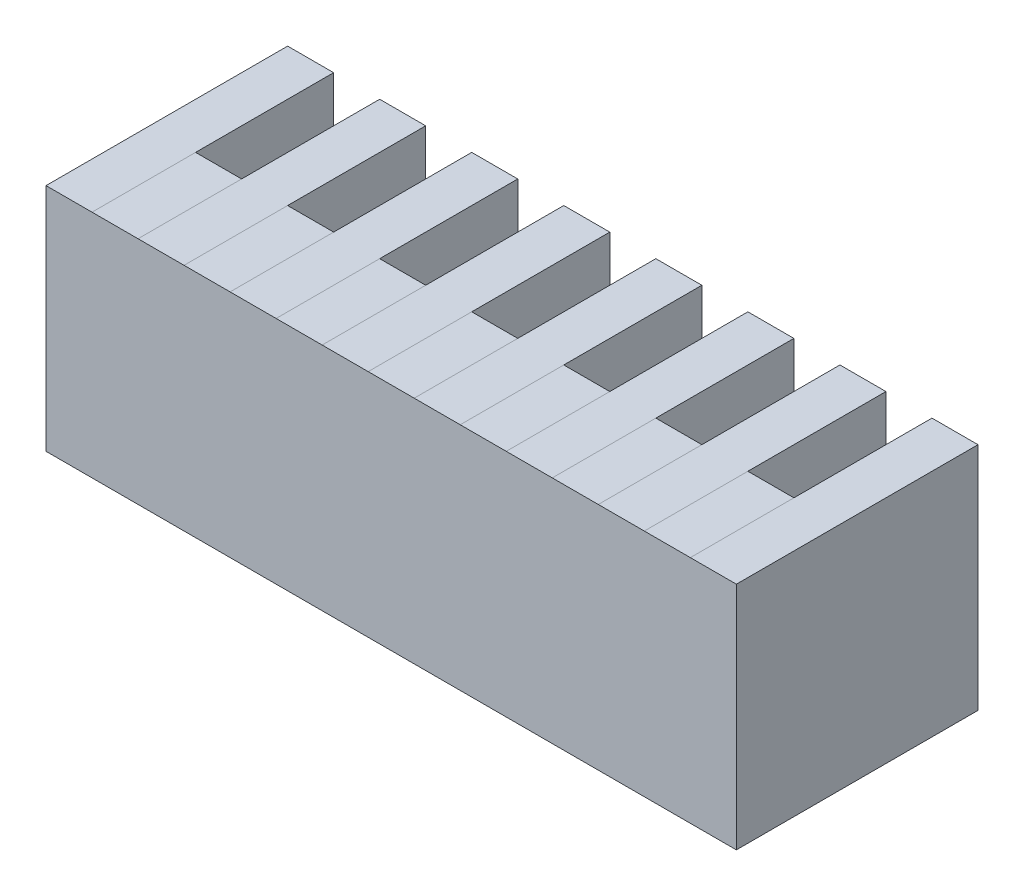
SolidWorks part; units mm, degrees
ref_plane "Front Plane" through (0, 0, 0) normal (0, 0, 1) x (1, 0, 0)
ref_plane "Top Plane" through (0, 0, 0) normal (0, 1, 0) x (1, 0, 0)
ref_plane "Right Plane" through (0, 0, 0) normal (1, 0, 0) x (0, 0, -1)
sketch "Sketch1" plane through (0, 0, 0) normal (0, 0, 1) x (1, 0, 0)
  line L1 (0, 0) -> (30, 0)
  line L2 (0, 0) -> (0, 10)
  line L3 (0, 10) -> (30, 10)
  line L4 (30, 0) -> (30, 10)
  dimension "D1" = 30
  dimension "D2" = 10
extrude "Boss-Extrude1" add sketch "Sketch1" along normal blind 10.5
sketch "Sketch3" plane through (0, 0, 0) normal (0, -1, 0) x (1, 0, 0)
  line L0 (0, 0) -> (30, 0) construction
  line L2 (2, 0) -> (2, 6)
  line L3 (2, 6) -> (4, 6)
  line L4 (4, 0) -> (4, 6)
  line L5 (0, 10.5) -> (0, 0) construction
  dimension "D1" = 2
  dimension "D2" = 2
  dimension "D3" = 6
extrude "Cut-Extrude1" cut sketch "Sketch3" against normal through all and the other way through all
pattern_linear "LPattern1" count 13 spacing 2 along (1, 0, 0) skipping (1, 0), (3, 0), (5, 0), (7, 0), (9, 0), (11, 0) of "Cut-Extrude1"
sketch "Sketch4" plane through (0, 0, 0) normal (0, -1, 0) x (1, 0, 0)
  line L0 (2, 6) -> (2, 10.5)
  line L1 (0, 10.5) -> (30, 10.5) construction
  line L2 (4, 6) -> (4, 10.5)
  line L3 (6, 6) -> (6, 10.5)
  line L4 (8, 6) -> (8, 10.5)
  line L5 (10, 6) -> (10, 10.5)
  line L6 (12, 6) -> (12, 10.5)
  line L7 (14, 6) -> (14, 10.5)
  line L8 (16, 6) -> (16, 10.5)
  line L9 (18, 6) -> (18, 10.5)
  line L10 (20, 6) -> (20, 10.5)
  line L11 (22, 6) -> (22, 10.5)
  line L12 (24, 6) -> (24, 10.5)
  line L13 (26, 6) -> (26, 10.5)
  line L14 (28, 6) -> (28, 10.5)
  dimension "D1" = 14
split line "Split Line1"
sketch "Sketch5" plane through (0, 10, 0) normal (0, 1, 0) x (1, 0, 0)
  line L0 (28, -6) -> (28, -10.5)
  line L1 (30, -10.5) -> (0, -10.5) construction
  line L2 (26, -6) -> (26, -10.5)
  line L3 (24, -6) -> (24, -10.5)
  line L4 (22, -6) -> (22, -10.5)
  line L5 (20, -6) -> (20, -10.5)
  line L6 (18, -6) -> (18, -10.5)
  line L7 (16, -6) -> (16, -10.5)
  line L8 (14, -6) -> (14, -10.5)
  line L9 (12, -6) -> (12, -10.5)
  line L10 (10, -6) -> (10, -10.5)
  line L11 (8, -6) -> (8, -10.5)
  line L12 (6, -6) -> (6, -10.5)
  line L13 (4, -6) -> (4, -10.5)
  line L14 (2, -6) -> (2, -10.5)
  dimension "D1" = 14
split line "Split Line2"
